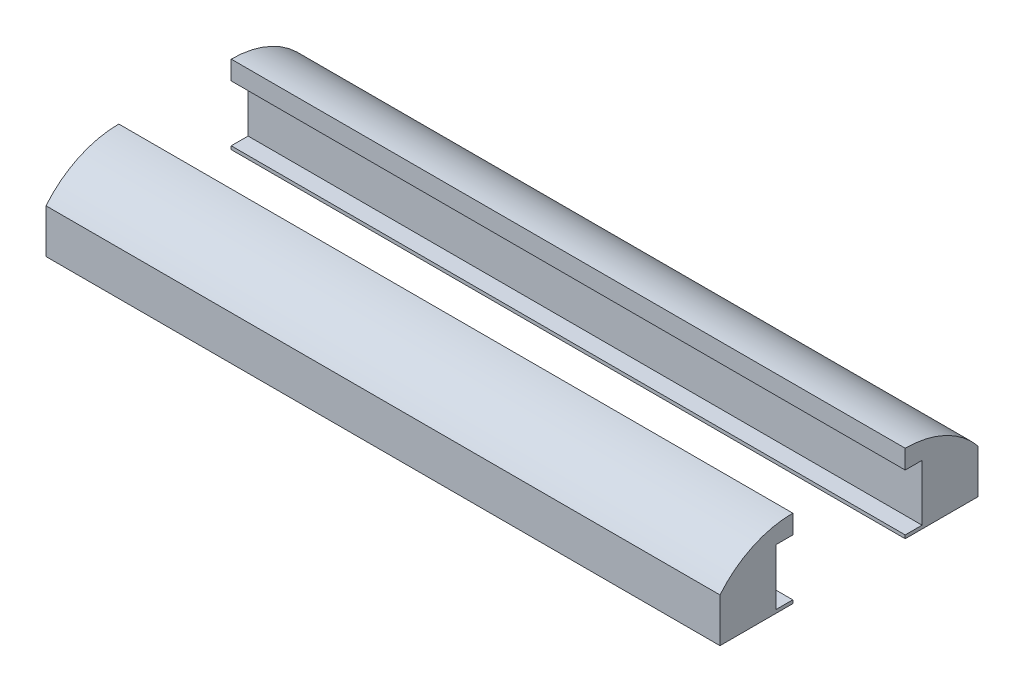
SolidWorks part; units mm, degrees
ref_plane "Front Plane" through (0, 0, 0) normal (0, 0, 1) x (1, 0, 0)
ref_plane "Top Plane" through (0, 0, 0) normal (0, 1, 0) x (1, 0, 0)
ref_plane "Right Plane" through (0, 0, 0) normal (1, 0, 0) x (0, 0, -1)
sketch "Sketch2" plane through (0, 0, 0) normal (0, 1, 0) x (1, 0, 0)
  line L0 (0, 0) -> (12, 0)
  line L1 (0, -10) -> (12, -10)
  line L2 (0, 10) -> (12, 10)
  dimension "D1" = 12
  dimension "D2" = 10
  dimension "D3" = 10
ref_plane "Plane1" through (0, 0, -10) normal (1, 0, 0) x (0, 0, -1)
sketch "Sketch3" plane through (0, 0, -10) normal (1, 0, 0) x (0, 0, -1)
  line L0 (0.0083, 0) -> (12.9683, 0)
  line L1 (12.9683, 0) -> (12.9683, 7.83)
  line L2 (0.0083, 0) -> (0.0083, 0.5948)
  line L3 (0.0083, 0.5948) -> (3.0083, 0.5948)
  line L4 (3.0083, 0.5948) -> (3.0083, 10.5948)
  line L5 (3.0083, 10.5948) -> (0.0083, 10.5948)
  line L6 (0.0083, 10.5948) -> (0.0083, 13.96)
  line L7 (-10, 0) -> (-10, 20.7377) construction
  line L8 (-20.0083, 10.5948) -> (-20.0083, 13.96)
  line L9 (-23.0083, 10.5948) -> (-20.0083, 10.5948)
  line L10 (-23.0083, 0.5948) -> (-23.0083, 10.5948)
  line L11 (-20.0083, 0.5948) -> (-23.0083, 0.5948)
  line L12 (-20.0083, 0) -> (-20.0083, 0.5948)
  line L13 (-20.0083, 0) -> (-32.9683, 0)
  line L14 (-32.9683, 0) -> (-32.9683, 7.83)
  arc A0 (0.0083, 13.96) -> (12.9683, 7.83) centre (0.0083, -2.805) cw
  arc A1 (-20.0083, 13.96) -> (-32.9683, 7.83) centre (-20.0083, -2.805) ccw
  point P13 (0.0083, 0)
  dimension "D6" = 16.765
  dimension "D1" = 3
  dimension "D2" = 12.96
  dimension "D3" = 10
  dimension "D4" = 13.96
  dimension "D5" = 7.83
extrude "Boss-Extrude1" add sketch "Sketch3" along normal blind 120
